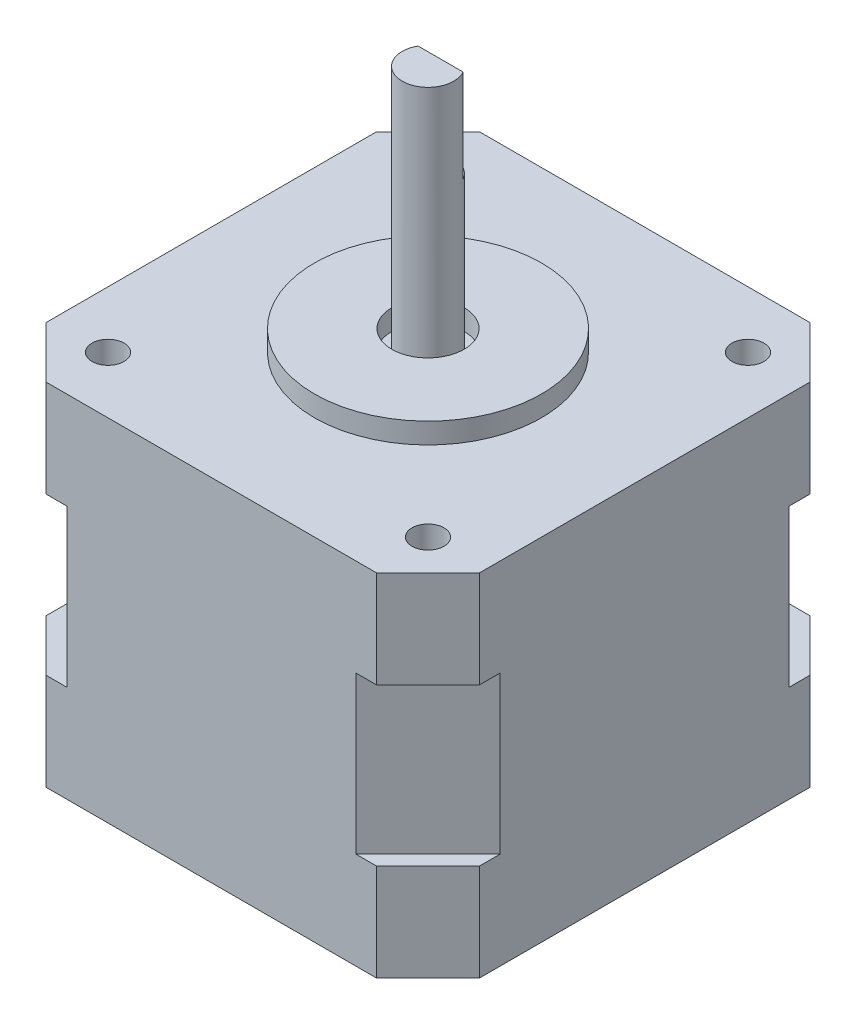
SolidWorks part; units mm, degrees
ref_plane "Front Plane" through (0, 0, 0) normal (0, 0, 1) x (1, 0, 0)
ref_plane "Top Plane" through (0, 0, 0) normal (0, 1, 0) x (1, 0, 0)
ref_plane "Right Plane" through (0, 0, 0) normal (1, 0, 0) x (0, 0, -1)
sketch "Sketch4" plane through (0, 0, 0) normal (0, 1, 0) x (1, 0, 0)
  line L1 (-21, -21) -> (21, -21)
  line L2 (-21, -21) -> (-21, 21)
  line L3 (-21, 21) -> (21, 21)
  line L4 (21, -21) -> (21, 21)
  line L5 (-21, -21) -> (21, 21) construction
  line L6 (-21, 21) -> (21, -21) construction
  point P0 (0, 0)
  dimension "D1" = 42
  dimension "D2" = 42
extrude "Bottom" add sketch "Sketch4" along normal blind 9.4 contours L2 L3 L4 L1
sketch "Sketch6" plane through (0, 9.4, 0) normal (0, 1, 0) x (1, 0, 0)
  line L0 (-21, -14) -> (-14, -21)
  line L1 (-14, -21) -> (14, -21)
  line L2 (-21, -14) -> (-21, 14)
  line L3 (-14, 21) -> (14, 21)
  line L4 (21, -14) -> (21, 14)
  line L5 (-21, -21) -> (21, 21) construction
  line L6 (-21, 21) -> (21, -21) construction
  line L7 (-21, 14) -> (-14, 21)
  line L8 (14, 21) -> (21, 14)
  line L9 (14, -21) -> (21, -14)
  point P0 (0, 0)
  dimension "D1" = 42
  dimension "D2" = 42
extrude "Middle" add sketch "Sketch6" along normal blind 15.2
sketch "Sketch8" plane through (0, 24.6, 0) normal (0, 1, 0) x (1, 0, 0)
  line L1 (-21, -21) -> (21, -21)
  line L2 (-21, -21) -> (-21, 21)
  line L3 (-21, 21) -> (21, 21)
  line L4 (21, -21) -> (21, 21)
  line L5 (-21, -21) -> (21, 21) construction
  line L6 (-21, 21) -> (21, -21) construction
  point P0 (0, 0)
  dimension "D1" = 42
  dimension "D2" = 42
extrude "Top" add sketch "Sketch8" along normal blind 9.4
chamfer "Chamfer1" distance 5 angle 45 8 edges at (21, 4.7, -21) (21, 29.3, -21) (-21, 4.7, 21) (21, 4.7, 21) (21, 29.3, 21) (-21, 29.3, 21) (-21, 4.7, -21) (-21, 29.3, -21)
sketch "Sketch9" plane through (0, 34, 0) normal (0, 1, 0) x (1, 0, 0)
  circle A0 centre (0, 0) radius 11
  circle A1 centre (0, 0) radius 3.5
  dimension "D1" = 22
  dimension "D2" = 7
extrude "Ring" add sketch "Sketch9" along normal blind 2 contours A0 | A1
sketch "Sketch10" plane through (0, 34, 0) normal (0, 1, 0) x (1, 0, 0)
  circle A0 centre (0, 0) radius 2.5
  dimension "D1" = 5
extrude "Shaft" add sketch "Sketch10" along normal blind 24
sketch "Sketch11" plane through (0, 0, 0) normal (1, 0, 0) x (0, 0, -1)
  line L0 (2.5, 34) -> (-2.5, 34) construction
  line L1 (3.4584, 73.2425) -> (1.2188, 73.2425)
  line L2 (3.4584, 73.2425) -> (3.4584, 49)
  line L3 (3.4584, 49) -> (1.2188, 49)
  line L4 (1.2188, 73.2425) -> (1.2188, 49)
  dimension "D1" = 15
extrude "Cut-Extrude3" cut sketch "Sketch11" against normal blind 5 and the other way blind 5
sketch "Sketch12" plane through (0, 34, 0) normal (0, 1, 0) x (1, 0, 0)
  line L0 (0, 0) -> (0, 23.6682) construction
  line L1 (0, 0) -> (27.1799, 0) construction
  circle A0 centre (15.5, -15.5) radius 1.55
  circle A1 centre (-15.5, -15.5) radius 1.55
  circle A2 centre (-15.5, 15.5) radius 1.55
  circle A3 centre (15.5, 15.5) radius 1.55
  dimension "D1" = 3.1
  dimension "D4" = 31
  dimension "D5" = 31
  dimension "D6" = 15.5
  dimension "D7" = 15.5
  dimension "D8" = 15.5
  dimension "D2" = 2
  dimension "D3" = 2
extrude "Cut-Extrude4" cut sketch "Sketch12" against normal blind 4.5 contours A0 | A1 | A2 | A3
sketch "Sketch13" plane through (0, 0, 0) normal (0, 0, 1) x (1, 0, 0)
  line L0 (0, 0) -> (0, 63.2226) construction
  line L1 (-16, 0) -> (16, 0) construction
sketch "Sketch15" plane through (0, 0, 0) normal (0, -1, 0) x (1, 0, 0)
  circle A0 centre (15.5, 15.5) radius 1.55
  circle A1 centre (15.5, -15.5) radius 1.55
  circle A2 centre (-15.5, 15.5) radius 1.55
  circle A3 centre (-15.5, -15.5) radius 1.55
  dimension "D1" = 3.1
  dimension "D2" = 3.1
  dimension "D3" = 3.1
  dimension "D4" = 3.1
  dimension "D7" = 31
  dimension "D5" = 31
  dimension "D6" = 31
  dimension "D8" = 15.5
  dimension "D9" = 15.5
  dimension "D10" = 15.5
  dimension "D11" = 15.5
  dimension "D12" = 31
extrude "Cut-Extrude5" cut sketch "Sketch15" against normal blind 10
